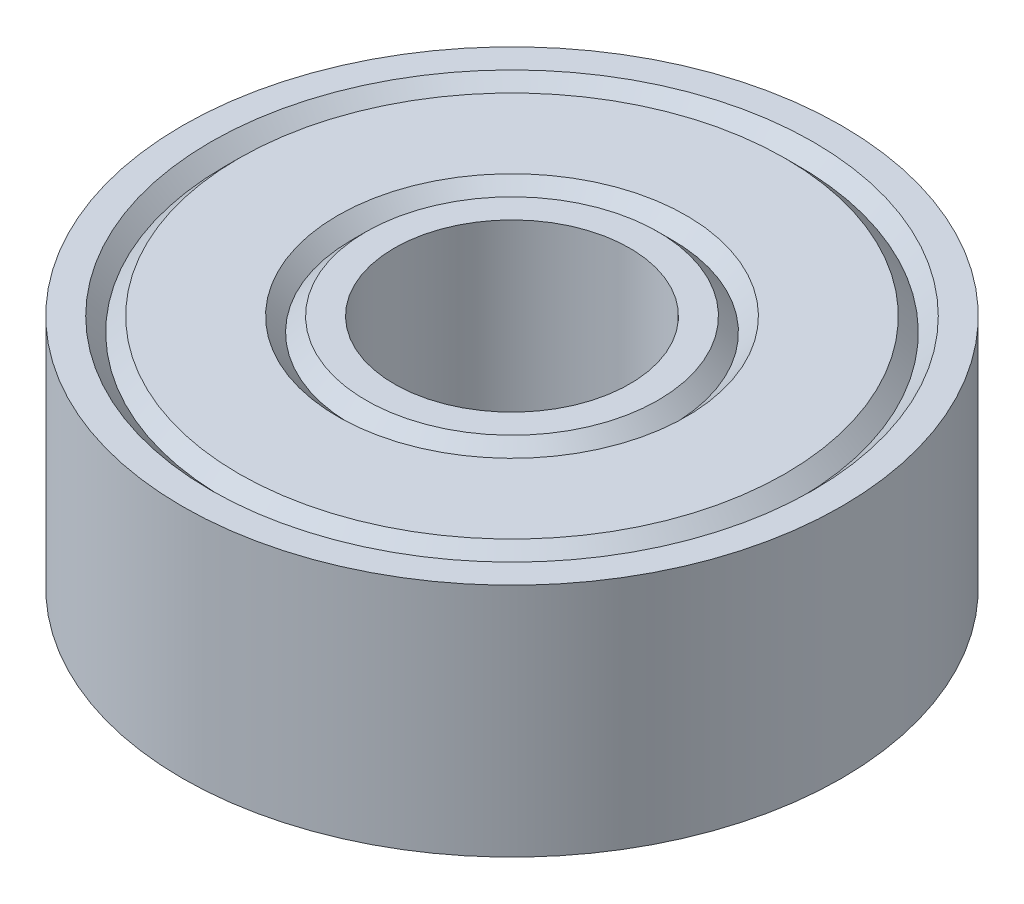
SolidWorks part; units mm, degrees
ref_plane "Front Plane" through (0, 0, 0) normal (0, 0, 1) x (1, 0, 0)
ref_plane "Top Plane" through (0, 0, 0) normal (0, 1, 0) x (1, 0, 0)
ref_plane "Right Plane" through (0, 0, 0) normal (1, 0, 0) x (0, 0, -1)
sketch "Sketch1" plane through (0, 0, 0) normal (0, 0, 1) x (1, 0, 0)
  line L0 (0, 2.5) -> (0, -2.5) construction
  line L1 (-2.5, 2.5) -> (-3.1, 2.5)
  line L2 (-2.5, 2.5) -> (-2.5, -2.5)
  line L3 (-2.5, -2.5) -> (-3.1, -2.5)
  line L4 (-7, 2.5) -> (-7, -2.5)
  line L5 (-6.4, 2.5) -> (-6.1, 2.2)
  line L6 (-6.1, 2.2) -> (-5.8, 2.5)
  line L7 (-3.7, 2.5) -> (-3.4, 2.2)
  line L8 (-3.4, 2.2) -> (-3.1, 2.5)
  line L9 (-6.4, -2.5) -> (-6.1, -2.2)
  line L10 (-6.1, -2.2) -> (-5.8, -2.5)
  line L11 (-3.7, -2.5) -> (-3.4, -2.2)
  line L12 (-3.4, -2.2) -> (-3.1, -2.5)
  line L13 (-3.7, -2.5) -> (-5.8, -2.5)
  line L14 (-6.4, -2.5) -> (-7, -2.5)
  line L15 (-6.4, 2.5) -> (-7, 2.5)
  line L16 (-3.7, 2.5) -> (-5.8, 2.5)
  line L17 (-6.1, 2.2) -> (-3.4, 2.2) construction
  line L18 (-6.1, 2.2) -> (-6.1, -2.2) construction
  line L19 (-3.4, -2.2) -> (-6.1, -2.2) construction
  line L20 (-3.4, 2.2) -> (-3.4, -2.2) construction
  line L21 (-6.1, 0) -> (-5.2, 0) construction
  line L22 (-3.1, 2.5) -> (-3.7, 2.5) construction
  line L23 (-5.2, 0) -> (-4.3, 0) construction
  line L24 (-6.1, 0) -> (-7, 0) construction
  line L25 (-4.3, 0) -> (-3.4, 0) construction
  line L26 (-3.4, 0) -> (-2.5, 0) construction
  dimension "D1" = 5
  dimension "D2" = 5
  dimension "D3" = 14
revolve "Revolve1" add sketch "Sketch1" angle 360 about L0
